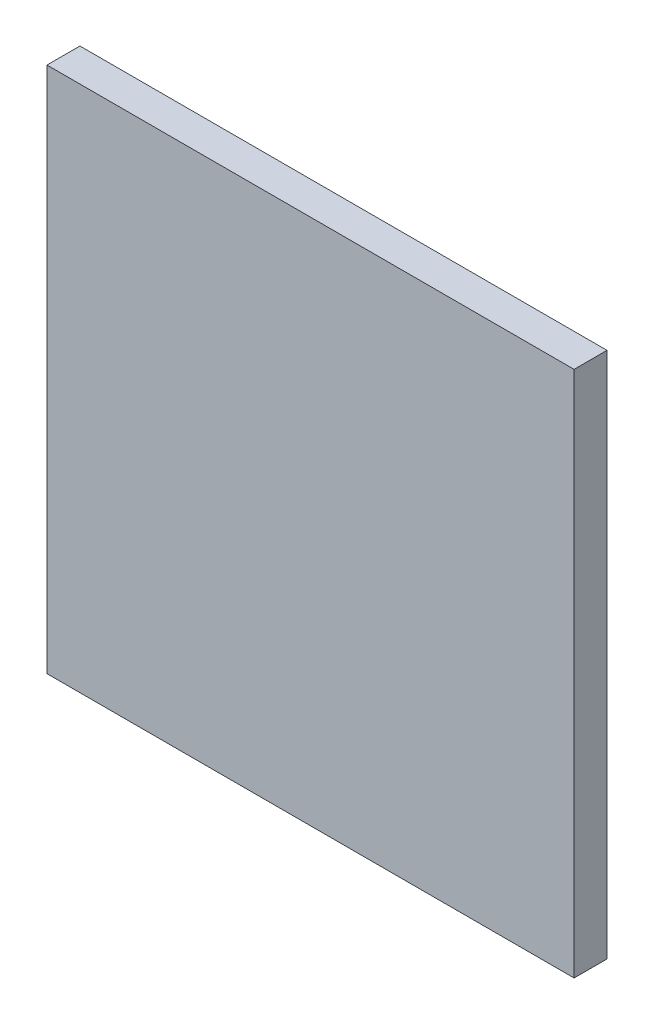
SolidWorks part; units mm, degrees
ref_plane "Front Plane" through (0, 0, 0) normal (0, 0, 1) x (1, 0, 0)
ref_plane "Top Plane" through (0, 0, 0) normal (0, 1, 0) x (1, 0, 0)
ref_plane "Right Plane" through (0, 0, 0) normal (1, 0, 0) x (0, 0, -1)
sketch "Sketch1" plane through (0, 0, 0) normal (0, 0, 1) x (1, 0, 0)
  line L1 (0, 0) -> (25.4, 0)
  line L2 (0, 0) -> (0, 25.4)
  line L3 (0, 25.4) -> (25.4, 25.4)
  line L4 (25.4, 0) -> (25.4, 25.4)
  point P5 (12.7, 12.7)
  dimension "D1" = 25.4
extrude "Boss-Extrude1" add sketch "Sketch1" along normal blind 1.5875
ref_point "Point1"
